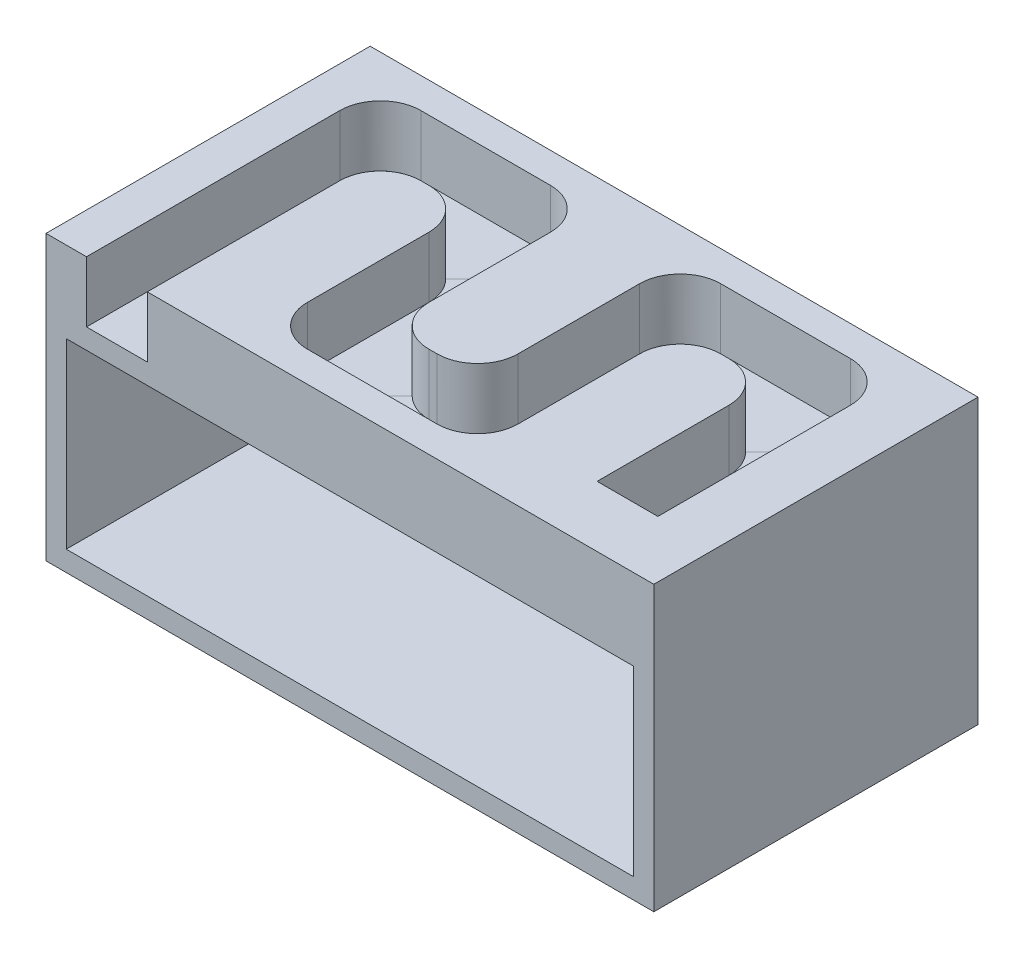
SolidWorks part; units mm, degrees
ref_plane "Front Plane" through (0, 0, 0) normal (0, 0, 1) x (1, 0, 0)
ref_plane "Top Plane" through (0, 0, 0) normal (0, 1, 0) x (1, 0, 0)
ref_plane "Right Plane" through (0, 0, 0) normal (1, 0, 0) x (0, 0, -1)
sketch "Sketch1" plane through (0, 0, 0) normal (0, 1, 0) x (1, 0, 0)
  line L1 (0, 0) -> (150, 0)
  line L2 (0, 0) -> (0, 80)
  line L3 (0, 80) -> (150, 80)
  line L4 (150, 0) -> (150, 80)
  dimension "D1" = 150
  dimension "D2" = 80
extrude "Boss-Extrude1" add sketch "Sketch1" along normal blind 70
shell "Shell1" thickness 5
sketch "Sketch2" plane through (0, 0, 0) normal (0, 0, 1) x (1, 0, 0)
  line L0 (0, 70) -> (150, 70) construction
  line L1 (10, 55) -> (25, 55)
  line L2 (10, 55) -> (10, 70)
  line L3 (10, 70) -> (25, 70)
  line L4 (25, 55) -> (25, 70)
  line L5 (0, 70) -> (0, 0) construction
  dimension "D1" = 15
  dimension "D2" = 15
  dimension "D3" = 10
sketch "Sketch3" plane through (0, 70, 0) normal (0, 1, 0) x (1, 0, 0)
  line L0 (17.5, 0) -> (17.5, 65)
  line L1 (10, 0) -> (25, 0) construction
  line L2 (17.5, 65) -> (54.5, 65)
  line L3 (54.5, 65) -> (54.5, 15)
  line L4 (54.5, 15) -> (91.5, 15)
  line L5 (91.5, 15) -> (91.5, 65)
  line L6 (91.5, 65) -> (128.5, 65)
  line L7 (128.5, 65) -> (128.5, 15)
  line L10 (150, 80) -> (0, 80) construction
  line L11 (54.5, 65) -> (54.5, 80) construction
  line L12 (128.5, 15) -> (128.5, 0) construction
  line L13 (0, 0) -> (150, 0) construction
  dimension "D1" = 37
  dimension "D2" = 15
sweep "Cut-Sweep1" cut profiles "Sketch2" path "Sketch3"
fillet "Fillet1" radius 10 12 edges at (62, 62.5, -22.5) (84, 62.5, -22.5) (84, 62.5, -72.5) (136, 62.5, -72.5) (121, 62.5, -57.5) (99, 62.5, -57.5) (99, 62.5, -7.5) (47, 62.5, -7.5) (47, 62.5, -57.5) (25, 62.5, -57.5) (62, 62.5, -72.5) (10, 62.5, -72.5)
